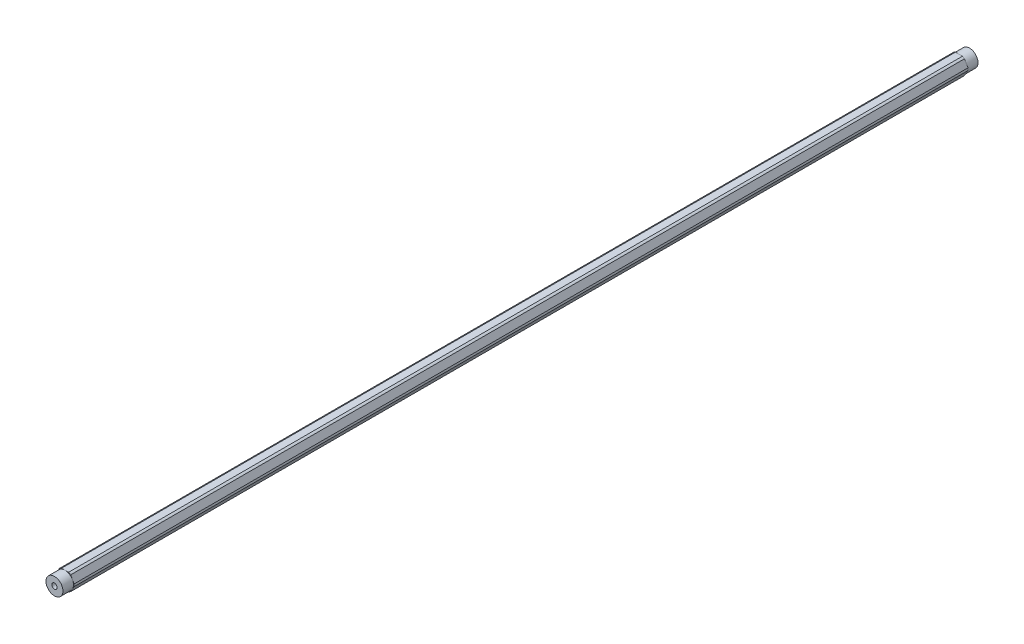
SolidWorks part; units mm, degrees
ref_plane "Front Plane" through (0, 0, 0) normal (0, 0, 1) x (1, 0, 0)
ref_plane "Top Plane" through (0, 0, 0) normal (0, 1, 0) x (1, 0, 0)
ref_plane "Right Plane" through (0, 0, 0) normal (1, 0, 0) x (0, 0, -1)
sketch "Sketch1" plane through (0, 0, 0) normal (0, 0, 1) x (1, 0, 0)
  line L1 (7.3323, 0) -> (3.6662, 6.35)
  line L2 (3.6662, 6.35) -> (-3.6662, 6.35)
  line L3 (-3.6662, 6.35) -> (-7.3323, 0)
  line L4 (-7.3323, 0) -> (-3.6662, -6.35)
  line L5 (-3.6662, -6.35) -> (3.6662, -6.35)
  line L6 (3.6662, -6.35) -> (7.3323, 0)
  circle A1 centre (0, 0) radius 6.35 construction
  dimension "D1" = 12.7
extrude "Boss-Extrude1" add sketch "Sketch1" along normal mid plane 685.8 contours L3 L4 L5 L6 L1 L2
sketch "Sketch2" plane through (0, 0, 342.9) normal (0, 0, 1) x (1, 0, 0)
  circle A0 centre (0, 0) radius 6.35
extrude "Cut-Extrude2" cut sketch "Sketch2" against normal blind 7.9502 flip side to cut
sketch "Sketch3" plane through (0, 0, 342.9) normal (0, 0, 1) x (1, 0, 0)
  circle A0 centre (0, 0) radius 6.875
  dimension "D1" = 13.75
extrude "Cut-Extrude4" cut sketch "Sketch3" against normal through all flip side to cut
mirror "Mirror1" about plane through (0, 0, 0) normal (0, 0, 1) of "Cut-Extrude2"
sketch "Sketch4" plane through (0, 0, 342.9) normal (0, 0, 1) x (1, 0, 0)
  circle A0 centre (0, 0) radius 2.0193
  dimension "D1" = 4.0386
extrude "Cut-Extrude5" cut sketch "Sketch4" against normal through all
